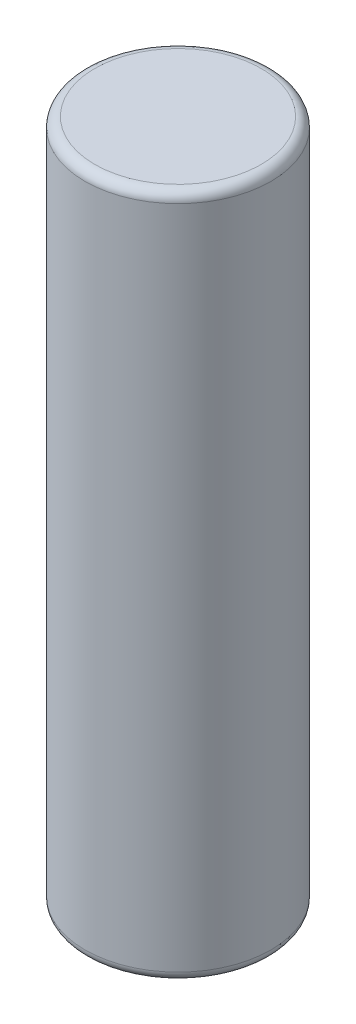
SolidWorks part; units mm, degrees
ref_plane "前视基准面" through (0, 0, 0) normal (0, 0, 1) x (1, 0, 0)
ref_plane "上视基准面" through (0, 0, 0) normal (0, 1, 0) x (1, 0, 0)
ref_plane "右视基准面" through (0, 0, 0) normal (1, 0, 0) x (0, 0, -1)
other "Configuration Table"
sketch "草图1" plane through (0, 0, 0) normal (0, 1, 0) x (1, 0, 0)
  circle A0 centre (0, 0) radius 9.5
  dimension "D1" = 19
extrude "凸台-拉伸1" add sketch "草图1" along normal blind 70
fillet "圆角1" radius 1 2 edges at (0, 0, 9.5) (0, 70, 9.5)
